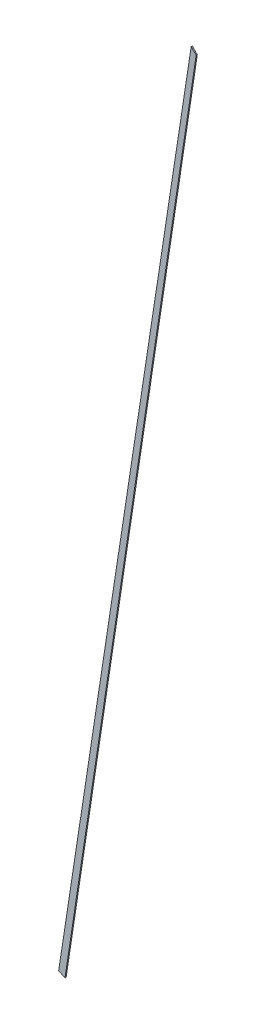
SolidWorks part; units mm, degrees
material "Custom Plastic"
ref_plane "X-Y Datum" through (0, 0, 0) normal (0, 0, 1) x (1, 0, 0)
ref_plane "X-Z Datum" through (0, 0, 0) normal (0, 1, 0) x (1, 0, 0)
ref_plane "Y-Z Datum" through (0, 0, 0) normal (1, 0, 0) x (0, 0, -1)
sketch "Sketch2" plane through (0, 0, 0) normal (0, 0, 1) x (1, 0, 0)
  line L5 (-296.0065, -566.0589) -> (60.5236, 1774.7071)
  line L8 (-304.5355, -561.8184) -> (-287.4775, -570.2993)
  line L9 (-287.4775, -570.2993) -> (67.2588, 1767.9719)
  line L10 (67.2588, 1767.9719) -> (53.7884, 1781.4423)
  line L11 (53.7884, 1781.4423) -> (-304.5355, -561.8184)
extrude "Boss-Extrude1" add sketch "Sketch2" along normal blind 3.175 contours L10 L11 L8 L5 | L9 L10 L5 L8
